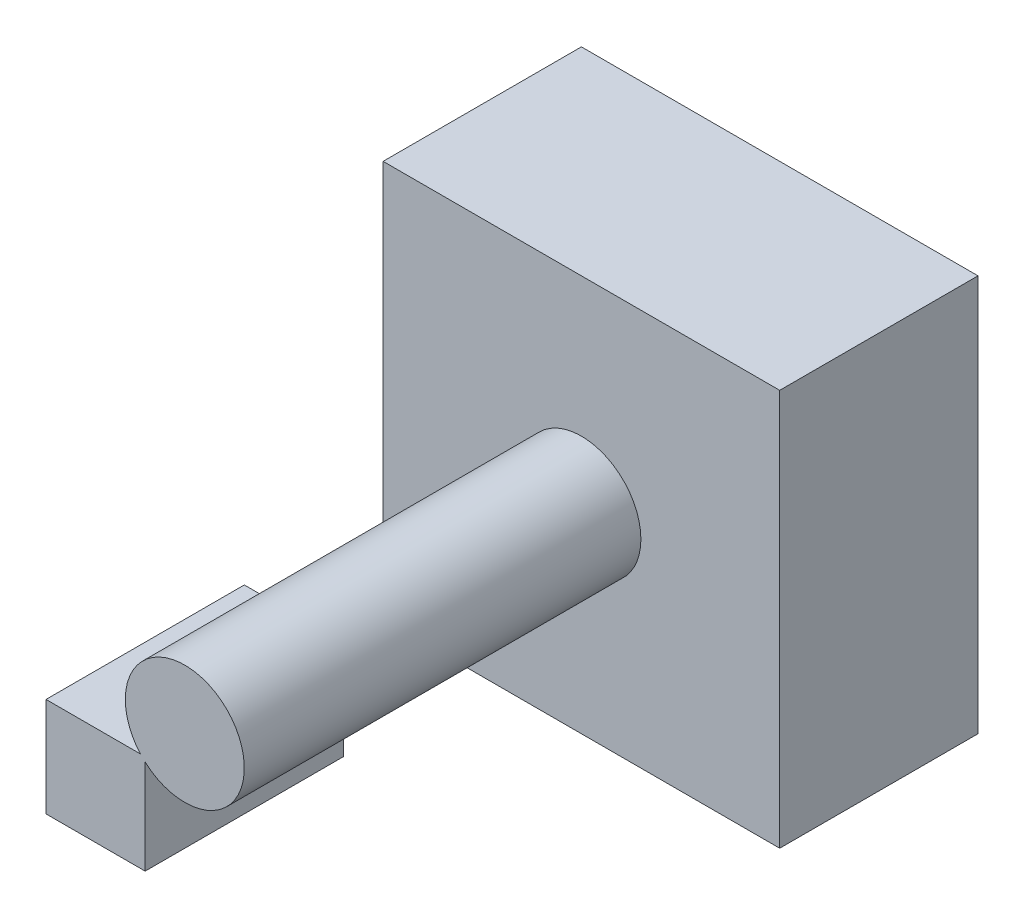
SolidWorks part; units mm, degrees
ref_plane "前视基准面" through (0, 0, 0) normal (0, 0, 1) x (1, 0, 0)
ref_plane "上视基准面" through (0, 0, 0) normal (0, 1, 0) x (1, 0, 0)
ref_plane "右视基准面" through (0, 0, 0) normal (1, 0, 0) x (0, 0, -1)
other "Configuration Table"
sketch "草图1" plane through (0, 0, 0) normal (0, 0, 1) x (1, 0, 0)
  line L1 (0, 0) -> (20, 0)
  line L2 (0, 0) -> (0, 20)
  line L3 (0, 20) -> (20, 20)
  line L4 (20, 0) -> (20, 20)
extrude "BaseBox" add sketch "草图1" along normal blind 10
ref_plane "基准面1" through (0, 0, 20) normal (0, 0, 1) x (1, 0, 0)
sketch "草图2" plane through (0, 0, 20) normal (0, 0, 1) x (1, 0, 0)
  line L1 (3, 3) -> (8, 3)
  line L2 (3, 3) -> (3, 8)
  line L3 (3, 8) -> (8, 8)
  line L4 (8, 3) -> (8, 8)
extrude "TargetBox" add sketch "草图2" along normal blind 10 separate body
sketch "草图3" plane through (0, 0, 10) normal (0, 0, 1) x (1, 0, 0)
  circle A0 centre (10, 10) radius 3
extrude "UpToVertexBoss" add sketch "草图3" along normal up to vertex (20 mm away) up to point (8, 3, 30)
